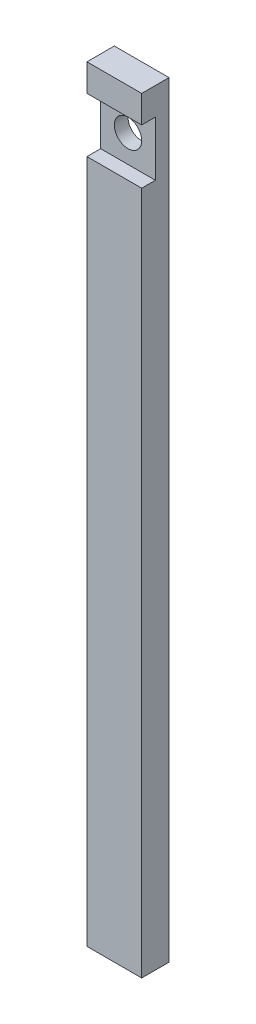
SolidWorks part; units mm, degrees
ref_plane "Front Plane" through (0, 0, 0) normal (0, 0, 1) x (1, 0, 0)
ref_plane "Top Plane" through (0, 0, 0) normal (0, 1, 0) x (1, 0, 0)
ref_plane "Right Plane" through (0, 0, 0) normal (1, 0, 0) x (0, 0, -1)
sketch "Sketch1" plane through (0, 0, 0) normal (0, 1, 0) x (1, 0, 0)
  line L1 (0, 0) -> (25.4, 0)
  line L2 (0, 0) -> (0, 12.7)
  line L3 (0, 12.7) -> (25.4, 12.7)
  line L4 (25.4, 0) -> (25.4, 12.7)
  dimension "D1" = 25.4
  dimension "D2" = 12.7
extrude "Boss-Extrude1" add sketch "Sketch1" along normal blind 355.6
sketch "Sketch2" plane through (25.4, 0, 0) normal (1, 0, 0) x (0, 0, -1)
  line L0 (0, 355.6) -> (0, 0) construction
  line L1 (0, 342.9) -> (6.35, 342.9)
  line L2 (0, 342.9) -> (0, 317.5)
  line L3 (0, 317.5) -> (6.35, 317.5)
  line L4 (6.35, 342.9) -> (6.35, 317.5)
  line L5 (0, 0) -> (12.7, 0) construction
  dimension "D1" = 6.35
  dimension "D2" = 25.4
  dimension "D3" = 317.5
extrude "Cut-Extrude1" cut sketch "Sketch2" against normal through all
sketch "Sketch3" plane through (0, 0, -6.35) normal (0, 0, 1) x (1, 0, 0)
  line L0 (0, 355.6) -> (25.4, 355.6) construction
  line L1 (25.4, 317.5) -> (25.4, 342.9) construction
  circle A0 centre (12.7, 330.2) radius 6.35
  point P4 (12.7, 355.6)
  point P7 (25.4, 330.2)
  dimension "D1" = 12.7
extrude "Cut-Extrude2" cut sketch "Sketch3" against normal through all
